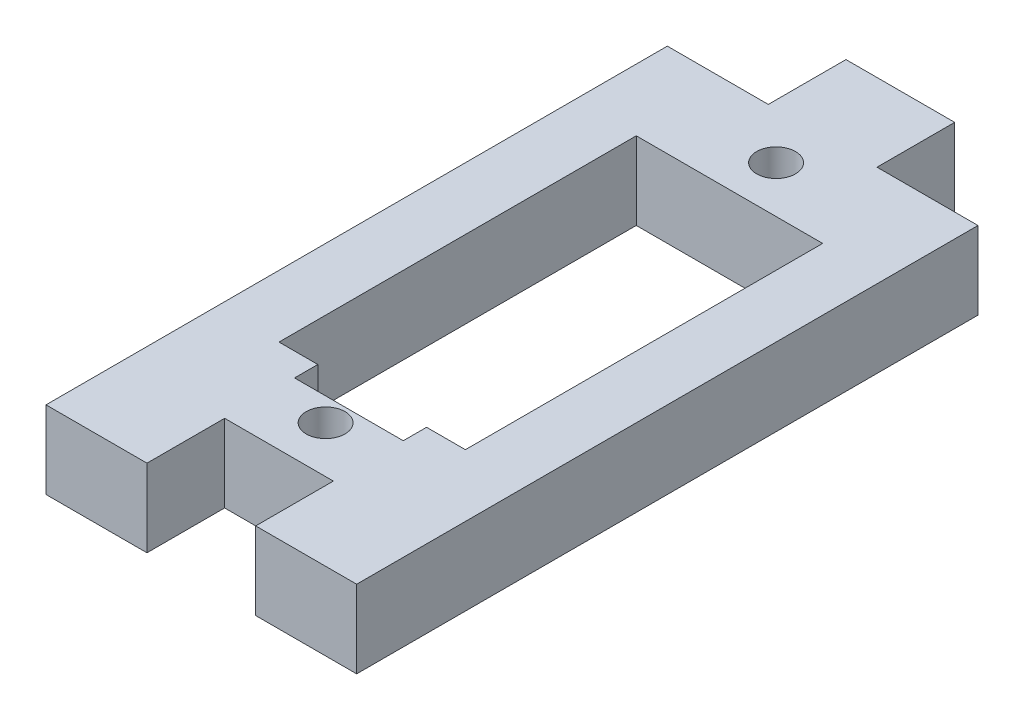
SolidWorks part; units mm, degrees
material "Acrylic (Medium-high impact)"
ref_plane "Front Plane" through (0, 0, 0) normal (0, 0, 1) x (1, 0, 0)
ref_plane "Top Plane" through (0, 0, 0) normal (0, 1, 0) x (1, 0, 0)
ref_plane "Right Plane" through (0, 0, 0) normal (1, 0, 0) x (0, 0, -1)
sketch "Sketch1" plane through (0, 0, 0) normal (0, 1, 0) x (1, 0, 0)
  line L0 (-10, 20) -> (-10, -20)
  line L1 (-10, -20) -> (-3.5, -20)
  line L2 (10, -20) -> (10, 20)
  line L3 (10, 20) -> (3.5, 20)
  line L4 (-3.5, 20) -> (-3.5, 25)
  line L5 (-3.5, 25) -> (3.5, 25)
  line L6 (3.5, 25) -> (3.5, 20)
  line L7 (-3.5, 20) -> (-10, 20)
  line L8 (-3.5, -20) -> (-3.5, -15)
  line L9 (-3.5, -15) -> (3.5, -15)
  line L10 (3.5, -15) -> (3.5, -20)
  line L11 (3.5, -20) -> (10, -20)
  point P12 (0, -15)
  point P13 (0, 25)
  point P18 (-10, 0)
  dimension "D1" = 45
  dimension "D2" = 5
  dimension "D3" = 5
  dimension "D4" = 7
  dimension "D5" = 20
  dimension "D6" = 10
extrude "Boss-Extrude1" add sketch "Sketch1" along normal blind 5
sketch "Sketch2" plane through (0, 5, 0) normal (0, 1, 0) x (1, 0, 0)
  line L0 (10, 20) -> (3.5, 20) construction
  line L1 (-6, 14) -> (6, 14)
  line L2 (-6, 14) -> (-6, -9)
  line L3 (-6, -9) -> (-3.5, -9)
  line L4 (6, 14) -> (6, -9)
  line L5 (-6, 14) -> (6, -9) construction
  line L6 (-6, -9) -> (6, 14) construction
  line L7 (-3.5, -15) -> (3.5, -15) construction
  line L8 (0, 17) -> (0, -12) construction
  line L9 (-3.5, 20) -> (-10, 20) construction
  line L10 (-3.5, -9) -> (-3.5, -10.5)
  line L11 (-3.5, -10.5) -> (3.5, -10.5)
  line L12 (3.5, -10.5) -> (3.5, -9)
  line L13 (3.5, -9) -> (6, -9)
  circle A0 centre (0, 17) radius 1.25
  circle A1 centre (0, -12) radius 1.25
  point P0 (0, 2.5)
  point P7 (0, 0)
  point P10 (0, -15)
  dimension "D6" = 2.5
  dimension "D1" = 23
  dimension "D2" = 12
  dimension "D3" = 6
  dimension "D4" = 29
  dimension "D5" = 3
  dimension "D7" = 7
  dimension "D8" = 3.5
  dimension "D9" = 1.5
extrude "Cut-Extrude1" cut sketch "Sketch2" against normal blind 5
